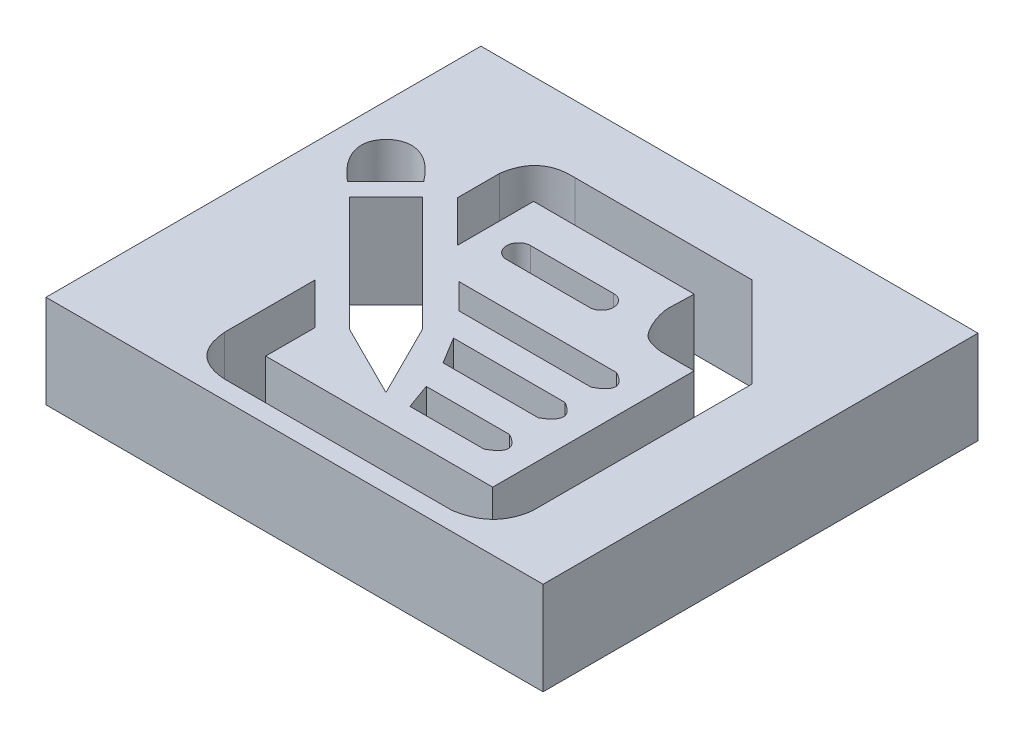
SolidWorks part; units mm, degrees
ref_plane "Front Plane" through (0, 0, 0) normal (0, 0, 1) x (1, 0, 0)
ref_plane "Top Plane" through (0, 0, 0) normal (0, 1, 0) x (1, 0, 0)
ref_plane "Right Plane" through (0, 0, 0) normal (1, 0, 0) x (0, 0, -1)
sketch "Sketch2" plane through (0, 0, 0) normal (0, 1, 0) x (1, 0, 0)
  line L1 (-42.8025, 22.3185) -> (-26.8025, 22.3185)
  line L2 (-42.8025, 22.3185) -> (-42.8025, 8.3185)
  line L3 (-42.8025, 8.3185) -> (-26.8025, 8.3185)
  line L4 (-26.8025, 22.3185) -> (-26.8025, 8.3185)
  dimension "D1" = 16
  dimension "D2" = 14
extrude "Boss-Extrude1" add sketch "Sketch2" along normal blind 3 contours L1 L4 L3 L2
sketch "Sketch4" plane through (0, 3, 0) normal (0, 1, 0) x (1, 0, 0)
  line L0 (44.0703, 264.4267) -> (385.4036, 264.4267) construction
  line L3 (122.1128, 434.8531) -> (775.4462, 434.8531) construction
  line L4 (-41.1756, 16.3949) -> (-39.9478, 17.6227)
  line L5 (-39.5307, 17.1703) -> (-40.7115, 15.9895)
  line L6 (-40.7115, 15.9895) -> (-37.0399, 12.3179)
  line L7 (-37.0399, 12.3179) -> (-34.6754, 11.1342)
  line L8 (-34.6754, 11.1342) -> (-35.8577, 13.5002)
  line L9 (-35.8577, 13.5002) -> (-39.5307, 17.1703)
  line L10 (-38.955, 17.7225) -> (-37.6274, 16.3949)
  line L11 (-37.6274, 16.3949) -> (-37.6274, 18.8387)
  line L12 (-37.6274, 18.8387) -> (-32.4578, 18.8387)
  line L13 (-30.3194, 16.7003) -> (-30.3194, 10.2148)
  line L14 (-30.3194, 10.2148) -> (-37.6274, 10.2148)
  line L15 (-37.6274, 10.2148) -> (-37.6274, 11.801)
  line L16 (-37.6274, 11.801) -> (-38.955, 13.1286)
  line L17 (-38.955, 13.1286) -> (-38.955, 10.2148)
  line L18 (-38.955, 17.7225) -> (-38.955, 19.0737)
  line L19 (-37.6274, 20.1663) -> (-31.929, 20.1663)
  line L20 (-31.929, 20.1663) -> (-29.0211, 17.2584)
  line L21 (-29.0211, 17.2584) -> (-29.0211, 10.2148)
  line L22 (-30.3194, 8.9107) -> (-37.6274, 8.9107)
  line L23 (-30.3194, 16.7003) -> (-31.4003, 16.7003)
  line L24 (-36.4407, 17.1703) -> (-33.7737, 17.1703) construction
  line L25 (-36.4407, 17.558) -> (-33.7737, 17.558)
  line L26 (-36.4407, 16.7826) -> (-33.7737, 16.7826)
  line L27 (-31.5178, 14.5855) -> (-35.7828, 14.5855)
  line L28 (-35.7828, 14.5855) -> (-36.5993, 15.4021)
  line L29 (-36.5993, 15.4021) -> (-31.5178, 15.4021)
  line L30 (-31.5178, 13.7396) -> (-35.1072, 13.7396)
  line L31 (-35.1072, 13.7396) -> (-34.5843, 12.8819)
  line L32 (-34.5843, 12.8819) -> (-31.5178, 12.8819)
  line L33 (-31.5178, 11.9537) -> (-34.1966, 11.9537)
  line L34 (-34.1966, 11.9537) -> (-33.9029, 11.1342)
  line L35 (-33.9029, 11.1342) -> (-31.5178, 11.1342)
  arc A0 (-36.4407, 17.558) -> (-36.4407, 16.7826) centre (-36.4407, 17.1703) ccw
  arc A1 (-33.7737, 16.7826) -> (-33.7737, 17.558) centre (-33.7737, 17.1703) ccw
  spline S0 degree 3 poles (-39.9478, 17.6227) (-40.7335, 18.6726) (-42.0964, 18.4054) (-42.1008, 17.1732) (-41.1756, 16.3949) knots 0 0 0 0 0.504616 1 1 1 1
  spline S1 degree 2 poles (-38.955, 10.2148) (-38.8557, 8.9744) (-37.6274, 8.9107) knots 0 0 0 1 1 1
  spline S2 degree 3 poles (-31.4003, 16.7003) (-31.826, 16.7591) (-32.1571, 16.9319) (-32.5633, 17.9914) (-32.4578, 18.2512) (-32.4578, 18.8387) knots 0 0 0 0 0.301446 0.62125 1 1 1 1
  spline S3 degree 2 poles (-31.5178, 11.1342) (-30.7657, 11.5534) (-31.5178, 11.9537) knots 0 0 0 1 1 1
  spline S4 degree 2 poles (-31.5178, 12.8819) (-30.7659, 13.3107) (-31.5178, 13.7396) knots 0 0 0 1 1 1
  spline S5 degree 2 poles (-31.5178, 14.5855) (-30.7659, 14.9938) (-31.5178, 15.4021) knots 0 0 0 1 1 1
  spline S6 degree 2 poles (-37.6274, 20.1663) (-38.793, 20.2183) (-38.955, 19.0737) knots 0 0 0 1 1 1
  spline S7 degree 2 poles (-30.3194, 8.9107) (-29.1467, 9.0957) (-29.0211, 10.2148) knots 0 0 0 1 1 1
  point P35 (-35.1072, 17.1703)
extrude "Cut-Extrude1" cut sketch "Sketch4" against normal blind 3
